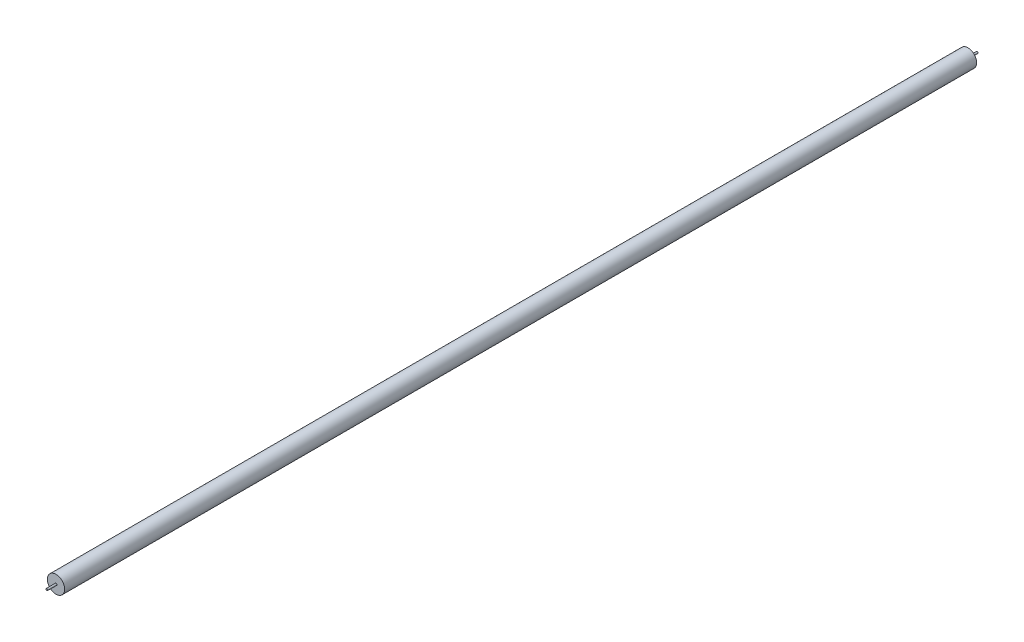
SolidWorks part; units mm, degrees
ref_plane "Front Plane" through (0, 0, 0) normal (0, 0, 1) x (1, 0, 0)
ref_plane "Top Plane" through (0, 0, 0) normal (0, 1, 0) x (1, 0, 0)
ref_plane "Right Plane" through (0, 0, 0) normal (1, 0, 0) x (0, 0, -1)
sketch "Sketch1" plane through (0, 0, 0) normal (0, 0, 1) x (1, 0, 0)
  circle A0 centre (0, 0) radius 4.75
  dimension "D1" = 9.5
extrude "Boss-Extrude1" add sketch "Sketch1" along normal blind 502
sketch "Sketch2" plane through (0, 0, 0) normal (0, 0, -1) x (-1, 0, 0)
  circle A0 centre (0, 0) radius 0.5
  dimension "D1" = 1
extrude "Boss-Extrude2" add sketch "Sketch2" along normal blind 5
sketch "Sketch3" plane through (0, 0, 502) normal (0, 0, 1) x (1, 0, 0)
  circle A0 centre (0, 0) radius 0.5
  dimension "D1" = 1
extrude "Boss-Extrude3" add sketch "Sketch3" along normal blind 5
